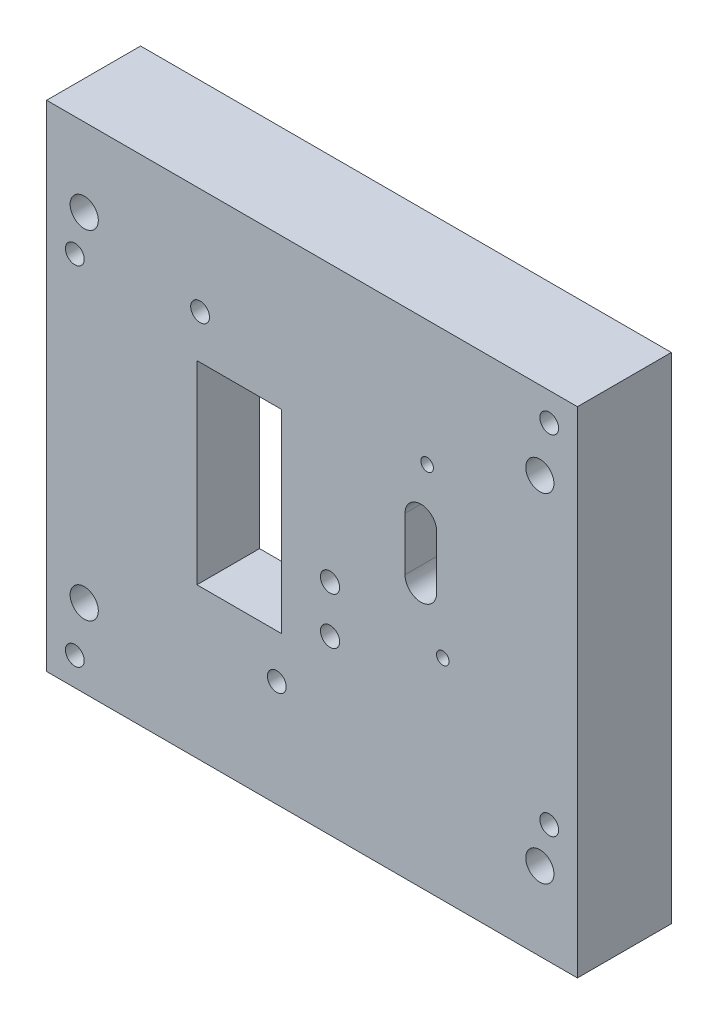
SolidWorks part; units mm, degrees
ref_plane "FP" through (0, 0, 0) normal (0, 0, 1) x (1, 0, 0)
ref_plane "TP" through (0, 0, 0) normal (0, 1, 0) x (1, 0, 0)
ref_plane "RP" through (0, 0, 0) normal (1, 0, 0) x (0, 0, -1)
ref_plane "Plane1" through (0, 0, 0) normal (0, 0, 1) x (1, 0, 0)
sketch "Sketch2" plane through (0, 0, 0) normal (0, 0, 1) x (1, 0, 0)
  line L1 (-119.5, 79) -> (50, 79)
  line L2 (-119.5, 79) -> (-119.5, -79)
  line L3 (-119.5, -79) -> (50, -79)
  line L4 (50, 79) -> (50, -79)
  line L8 (-92.5, 54) -> (-24, 54) construction
  line L9 (-24, -54) -> (-92.5, -54) construction
  line L10 (-94.5, -52) -> (-94.5, 52) construction
  line L11 (25, 45) -> (25, -18) construction
  dimension "D1" = 25
  dimension "D2" = 25
  dimension "D3" = 25
  dimension "D4" = 25
extrude "Boss-Extrude1" add sketch "Sketch2" along normal blind 30
sketch "Sketch4" plane through (0, 0, 0) normal (0, 0, -1) x (-1, 0, 0)
  line L5 (-5.06, 22) -> (-5.06, 5) construction
  line L6 (5.06, 5) -> (5.06, 22) construction
  line L7 (-5.06, 22) -> (-5.06, 5)
  line L8 (5.06, 5) -> (5.06, 22)
  line L9 (71.5, 31) -> (44.5, 31)
  line L10 (71.5, -31) -> (71.5, 31)
  line L11 (44.5, -31) -> (71.5, -31)
  line L12 (44.5, 31) -> (44.5, -31)
  line L13 (71.5, 31) -> (44.5, 31)
  line L14 (71.5, -31) -> (71.5, 31)
  line L15 (44.5, -31) -> (71.5, -31)
  line L16 (44.5, 31) -> (44.5, -31)
  circle A0 centre (29, -9) radius 3.06 construction
  circle A1 centre (29, -9) radius 3.06
  circle A2 centre (29, -24) radius 3.06 construction
  circle A3 centre (29, -24) radius 3.06
  arc A4 (-5.06, 5) -> (5.06, 5) centre (0, 5) ccw construction
  arc A5 (5.06, 22) -> (-5.06, 22) centre (0, 22) ccw construction
  arc A6 (-5.06, 5) -> (5.06, 5) centre (0, 5) ccw
  arc A7 (5.06, 22) -> (-5.06, 22) centre (0, 22) ccw
  dimension "D1" = 0
extrude "Cut-Extrude2" cut sketch "Sketch4" against normal through all from offset 10 offset against normal yes
sketch "Sketch5" plane through (0, 0, 0) normal (0, 0, -1) x (-1, 0, 0)
  line L4 (-25, 45) -> (-25, -18)
  line L5 (-23, -20) -> (14, -20)
  line L6 (16, -18) -> (16, 45)
  line L7 (14, 47) -> (-23, 47)
  line L8 (-25, 45) -> (-25, -18)
  line L9 (-23, -20) -> (14, -20)
  line L10 (16, -18) -> (16, 45)
  line L11 (14, 47) -> (-23, 47)
  line L12 (24, -54) -> (92.5, -54)
  line L13 (94.5, -52) -> (94.5, 52)
  line L14 (92.5, 54) -> (24, 54)
  line L15 (22, 52) -> (22, -52)
  line L16 (24, -54) -> (92.5, -54)
  line L17 (94.5, -52) -> (94.5, 52)
  line L18 (92.5, 54) -> (24, 54)
  line L19 (22, 52) -> (22, -52)
  arc A4 (-23, 47) -> (-25, 45) centre (-23, 45) ccw
  arc A5 (-23, 47) -> (-25, 45) centre (-23, 45) ccw
  arc A6 (-25, -18) -> (-23, -20) centre (-23, -18) ccw
  arc A7 (-25, -18) -> (-23, -20) centre (-23, -18) ccw
  arc A8 (14, -20) -> (16, -18) centre (14, -18) ccw
  arc A9 (14, -20) -> (16, -18) centre (14, -18) ccw
  arc A10 (16, 45) -> (14, 47) centre (14, 45) ccw
  arc A11 (16, 45) -> (14, 47) centre (14, 45) ccw
  arc A12 (24, 54) -> (22, 52) centre (24, 52) ccw
  arc A13 (24, 54) -> (22, 52) centre (24, 52) ccw
  arc A14 (22, -52) -> (24, -54) centre (24, -52) ccw
  arc A15 (22, -52) -> (24, -54) centre (24, -52) ccw
  arc A16 (92.5, -54) -> (94.5, -52) centre (92.5, -52) ccw
  arc A17 (92.5, -54) -> (94.5, -52) centre (92.5, -52) ccw
  arc A18 (94.5, 52) -> (92.5, 54) centre (92.5, 52) ccw
  arc A19 (94.5, 52) -> (92.5, 54) centre (92.5, 52) ccw
  dimension "D1" = 0
  dimension "D2" = 0
extrude "Cut-Extrude4" cut sketch "Sketch5" against normal blind 10
ref_plane "Plane2" through (0, 0, 0) normal (0, 0, -1) x (-1, 0, 0)
sketch "Sketch9" plane through (0, 0, 0) normal (0, 0, -1) x (-1, 0, 0)
  line L2 (16, -18) -> (16, 45) construction
  circle A0 centre (19, 25) radius 2
  circle A1 centre (19, -25) radius 2
  dimension "D1" = 4
  dimension "D2" = 1
  dimension "D3" = 50
  dimension "D4" = 25
extrude "Cut-Extrude14" cut sketch "Sketch9" against normal blind 15
ref_plane "Plane3" through (0, 0, 15) normal (0, 0, -1) x (-1, 0, 0)
sketch "Sketch11" plane through (0, 0, 15) normal (0, 0, -1) x (-1, 0, 0)
  circle A9 centre (19, 25) radius 3
  circle A10 centre (19, 25) radius 3
  circle A12 centre (19, -25) radius 3
  circle A13 centre (19, -25) radius 3
  dimension "D1" = 1
  dimension "D2" = 1
extrude "Cut-Extrude16" cut sketch "Sketch11" against normal blind 7.5
hole_wizard "CBORE for M8 SHCS1" positions "Sketch12" profile "Sketch13" counterbore size "M8" standard "ANSI Metric" end condition through all
sketch "Sketch12" plane through (0, 0, 0) normal (0, 0, -1) x (-0.9063, -0.4226, 0)
  point P0 (74.6067, 94.3721)
  point P1 (120.2495, -3.5092)
  point P2 (-57.2611, 32.8811)
  point P3 (-11.6183, -65.0001)
sketch "Sketch13" plane through (-107.5, 54, 0) normal (1, 0, 0) x (0, 1, 0)
  line L0 (0, 0) -> (0, 30)
  line L1 (0, 30) -> (4.5, 30)
  line L2 (4.5, 30) -> (4.5, 8)
  line L3 (4.5, 8) -> (7.5, 8)
  line L4 (7.5, 8) -> (7.5, 0)
  line L5 (7.5, 0) -> (0, 0)
  line L6 (0, -6.35) -> (0, 107.95) construction
  dimension "Thru Hole Dia." = 9
  dimension "Thru Hole Depth" = 30
  dimension "C'Bore Dia." = 15
  dimension "C'Bore Depth" = 8
hole_wizard "M8x1.25 Tapped Hole1" positions "Sketch14" profile "Sketch15" tap size "M8x1.25" standard "ANSI Metric"
sketch "Sketch14" plane through (0, 0, 10) normal (0, 0, -1) x (-0.9063, -0.4226, 0)
  point P0 (57.0204, 72.9309)
  point P1 (13.0645, 52.4339)
  point P2 (48.5644, -23.6959)
  point P3 (92.5204, -3.1989)
sketch "Sketch15" plane through (-82.5, 42, 10) normal (1, 0, 0) x (0, 1, 0)
  line L0 (0, 0) -> (0, 14.0429)
  line L1 (0, 14.0429) -> (3.4, 12)
  line L2 (3.4, 12) -> (3.4, 0)
  line L3 (3.4, 0) -> (0, 0)
  line L4 (0, 14.0429) -> (-3.4, 12) construction
  line L5 (0, -6.35) -> (0, 107.95) construction
  dimension "Tap Drill Dia." = 6.8
  dimension "Tap Drill Depth" = 12
  dimension "Drill Angle" = 118
cosmetic thread "Hole Thread1" parameters "D1"=10.75, "D2"=8
cosmetic thread "Hole Thread2" parameters "D1"=10.75, "D2"=8
cosmetic thread "Hole Thread3" parameters "D1"=10.75, "D2"=8
cosmetic thread "Hole Thread4" parameters "D1"=10.75, "D2"=8
hole_wizard "M6x1.0 Tapped Hole1" positions "Sketch16" profile "Sketch17" tap size "M6x1.0" standard "ANSI Metric"
sketch "Sketch16" plane through (0, 0, 10) normal (0, 0, -1) x (-0.9063, -0.4226, 0)
  point P0 (-30.5604, 27.6778)
  point P1 (10.993, -7.0111)
  point P2 (-9.8521, -16.7313)
  point P3 (-9.7153, 37.398)
sketch "Sketch17" plane through (16, 38, 10) normal (1, 0, 0) x (0, 1, 0)
  line L0 (0, 0) -> (0, 13.5022)
  line L1 (0, 13.5022) -> (2.5, 12)
  line L2 (2.5, 12) -> (2.5, 0)
  line L3 (2.5, 0) -> (0, 0)
  line L4 (0, 13.5022) -> (-2.5, 12) construction
  line L5 (0, -6.35) -> (0, 107.95) construction
  dimension "Tap Drill Dia." = 5
  dimension "Tap Drill Depth" = 12
  dimension "Drill Angle" = 118
cosmetic thread "Hole Thread5" parameters "D1"=11, "D2"=6
cosmetic thread "Hole Thread6" parameters "D1"=11, "D2"=6
cosmetic thread "Hole Thread7" parameters "D1"=11, "D2"=6
cosmetic thread "Hole Thread8" parameters "D1"=11, "D2"=6
hole_wizard "M6x1.0 Tapped Hole2" positions "Sketch19" profile "Sketch20" tap size "M6x1.0" standard "ANSI Metric"
sketch "Sketch19" plane through (0, 0, 0) normal (0, 0, -1) x (-0.9063, -0.4226, 0)
  point P0 (101.6347, -29.8434)
  point P1 (20.5202, -67.6677)
  point P2 (8.3065, -41.4754)
cosmetic thread "Hole Thread9" parameters "D1"=11, "D2"=6
cosmetic thread "Hole Thread10" parameters "D1"=11, "D2"=6
cosmetic thread "Hole Thread11" parameters "D1"=11, "D2"=6
sketch "Sketch20" plane through (-79.5, -70, 0) normal (1, 0, 0) x (0, 1, 0)
  line L0 (0, 0) -> (0, 13.5022)
  line L1 (0, 13.5022) -> (2.5, 12)
  line L2 (2.5, 12) -> (2.5, 0)
  line L3 (2.5, 0) -> (0, 0)
  line L4 (0, 13.5022) -> (-2.5, 12) construction
  line L5 (0, -6.35) -> (0, 107.95) construction
  dimension "Tap Drill Dia." = 5
  dimension "Tap Drill Depth" = 12
  dimension "Drill Angle" = 118
hole_wizard "M6x1.0 Tapped Hole3" positions "Sketch23" profile "Sketch24" tap size "M6x1.0" standard "ANSI Metric"
sketch "Sketch23" plane through (0, 0, 0) normal (0, 0, -1) x (-0.9063, -0.4226, 0)
  point P0 (42.4682, 97.0397)
  point P1 (-32.7297, 46.5271)
  point P2 (-38.6464, 59.2154)
sketch "Sketch24" plane through (-79.5, 70, 0) normal (1, 0, 0) x (0, 1, 0)
  line L0 (0, 0) -> (0, 13.5022)
  line L1 (0, 13.5022) -> (2.5, 12)
  line L2 (2.5, 12) -> (2.5, 6.5)
  line L3 (2.5, 6.5) -> (3, 6.5)
  line L4 (3, 6.5) -> (3, 0)
  line L5 (3, 0) -> (0, 0)
  line L10 (0, 13.5022) -> (-2.5, 12) construction
  line L11 (0, -6.35) -> (0, 107.95) construction
  dimension "Tap Drill Dia." = 5
  dimension "Tap Drill Depth" = 12
  dimension "Thread Major Dia." = 6
  dimension "Drill Angle" = 118
  dimension "Thread Depth Difference" = 5.5
hole_wizard "Ø6.0mm Clearance Dowel Hole1" positions "Sketch25" profile "Sketch26" hole size "Ø6.0" standard "ANSI Metric" end condition through all
sketch "Sketch25" plane through (0, 0, 0) normal (0, 0, -1) x (-0.9063, -0.4226, 0)
  point P0 (-66.7419, 46.1142)
  point P1 (82.8197, 83.8579)
sketch "Sketch26" plane through (41, 70, 0) normal (1, 0, 0) x (0, 1, 0)
  line L0 (0, 0) -> (0, 30)
  line L1 (0, 30) -> (3, 30)
  line L2 (3, 30) -> (3, 0)
  line L3 (3, 0) -> (0, 0)
  line L4 (0, -6.35) -> (0, 107.95) construction
  dimension "Thru Hole Dia." = 6
  dimension "Thru Hole Depth" = 30
hole_wizard "Ø6.0mm Clearance Dowel Hole2" positions "Sketch27" profile "Sketch28" hole size "Ø6.0" standard "ANSI Metric" end condition through all
sketch "Sketch27" plane through (0, 0, 0) normal (0, 0, -1) x (-0.9063, -0.4226, 0)
  point P0 (-19.789, -54.5766)
  point P1 (129.7303, -16.7422)
sketch "Sketch28" plane through (41, -41.1, 0) normal (1, 0, 0) x (0, 1, 0)
  line L0 (0, 0) -> (0, 30)
  line L1 (0, 30) -> (3, 30)
  line L2 (3, 30) -> (3, 0)
  line L3 (3, 0) -> (0, 0)
  line L4 (0, -6.35) -> (0, 107.95) construction
  dimension "Thru Hole Dia." = 6
  dimension "Thru Hole Depth" = 30
hole_wizard "Ø6.0mm Clearance Dowel Hole3" positions "Sketch29" profile "Sketch30" hole size "Ø6.0" standard "ANSI Metric" end condition through all
sketch "Sketch29" plane through (0, 0, 10) normal (0, 0, -1) x (-0.9063, -0.4226, 0)
  point P0 (44.8769, 70.5784)
  point P1 (60.708, -21.3434)
sketch "Sketch30" plane through (-70.5, 45, 10) normal (1, 0, 0) x (0, 1, 0)
  line L0 (0, 0) -> (0, 20)
  line L1 (0, 20) -> (3, 20)
  line L2 (3, 20) -> (3, 0)
  line L3 (3, 0) -> (0, 0)
  line L4 (0, -6.35) -> (0, 107.95) construction
  dimension "Thru Hole Dia." = 6
  dimension "Thru Hole Depth" = 20
hole_wizard "Ø4.0mm Clearance Dowel Hole1" positions "Sketch31" profile "Sketch32" hole size "Ø4.0" standard "ANSI Metric" end condition through all
sketch "Sketch31" plane through (0, 0, 10) normal (0, 0, -1) x (-0.9063, -0.4226, 0)
  point P0 (-18.2947, 34.5008)
  point P1 (-1.2727, -13.834)
sketch "Sketch32" plane through (2, 39, 10) normal (1, 0, 0) x (0, 1, 0)
  line L0 (0, 0) -> (0, 20)
  line L1 (0, 20) -> (2, 20)
  line L2 (2, 20) -> (2, 0)
  line L3 (2, 0) -> (0, 0)
  line L4 (0, -6.35) -> (0, 107.95) construction
  dimension "Thru Hole Dia." = 4
  dimension "Thru Hole Depth" = 20
